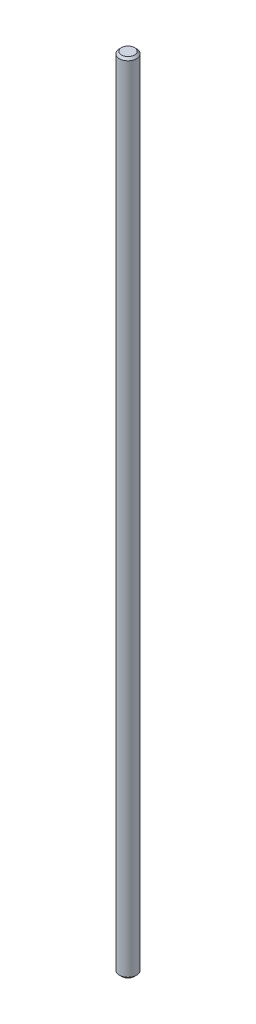
SolidWorks part; units mm, degrees
ref_plane "前基準面" through (0, 0, 0) normal (0, 0, 1) x (1, 0, 0)
ref_plane "上基準面" through (0, 0, 0) normal (0, 1, 0) x (1, 0, 0)
ref_plane "右基準面" through (0, 0, 0) normal (1, 0, 0) x (0, 0, -1)
sketch "草圖1" plane through (0, 0, 0) normal (0, 1, 0) x (1, 0, 0)
  circle A0 centre (0, 0) radius 4000
  dimension "D1" = 8000
extrude "填料-伸長1" add sketch "草圖1" along normal blind 370000
chamfer "導角1" distance 1000 angle 45 2 edges at (0, 0, 4000) (0, 370000, 4000)
